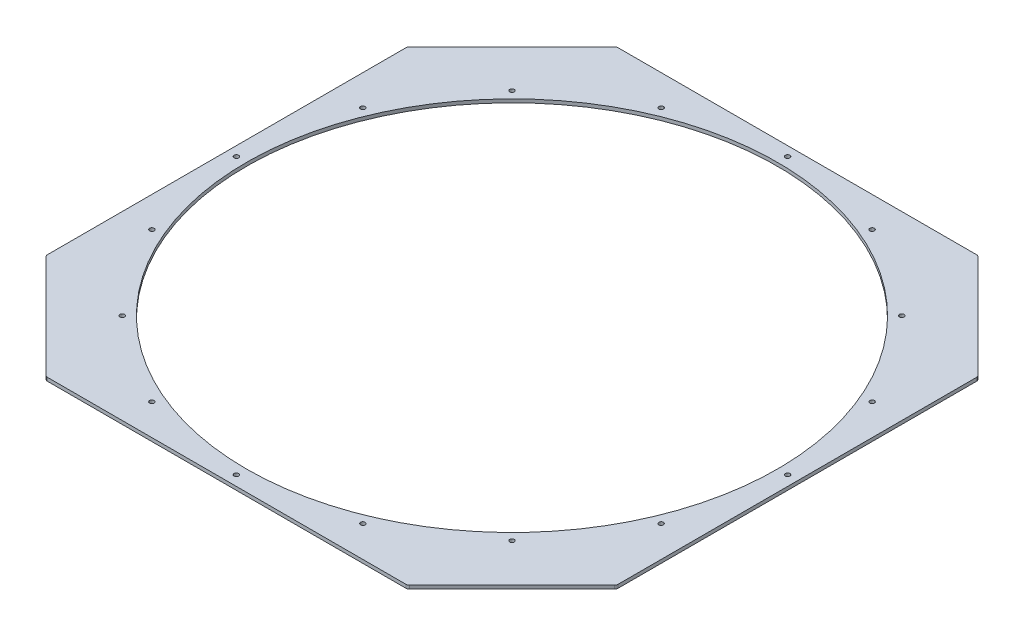
SolidWorks part; units mm, degrees
material "ASTM A36 Steel"
ref_plane "Front Plane" through (0, 0, 0) normal (0, 0, 1) x (1, 0, 0)
ref_plane "Top Plane" through (0, 0, 0) normal (0, 1, 0) x (1, 0, 0)
ref_plane "Right Plane" through (0, 0, 0) normal (1, 0, 0) x (0, 0, -1)
sketch "Sketch1" plane through (0, 0, 0) normal (0, 1, 0) x (1, 0, 0)
  line L11 (315.0665, 496.5) -> (497.5, 314.0665)
  line L13 (497.5, -315.0665) -> (315.0665, -497.5)
  line L15 (-314.0665, -497.5) -> (-496.5, -315.0665)
  line L17 (-496.5, 314.0665) -> (-314.0665, 496.5)
  line L19 (-314.0665, -497.5) -> (315.0665, -497.5)
  line L20 (-496.5, -315.0665) -> (-496.5, 314.0665)
  line L21 (-314.0665, 496.5) -> (315.0665, 496.5)
  line L22 (497.5, -315.0665) -> (497.5, 314.0665)
  line L23 (-405.7832, -405.7832) -> (405.7832, 405.7832) construction
  line L24 (-405.2832, 405.2832) -> (406.2832, -406.2832) construction
  point P6 (0, 0)
  dimension "D2" = 994
  dimension "D3" = 258
  dimension "D4" = 45
  dimension "D5" = 258
  dimension "D6" = 45
  dimension "260" = 258
  dimension "D8" = 45
  dimension "D9" = 258
  dimension "D10" = 135
  dimension "D11" = 994
  dimension "D12" = 497.5
  dimension "D13" = 497.5
extrude "Boss-Extrude1" add sketch "Sketch1" along normal blind 6
sketch "Sketch2" plane through (0, 6, 0) normal (0, 1, 0) x (1, 0, 0)
  circle A0 centre (0, 0) radius 462.5
  dimension "D1" = 925
extrude "Cut-Extrude1" cut sketch "Sketch2" against normal blind 10
sketch "Sketch3" plane through (0, 6, 0) normal (0, 1, 0) x (1, 0, 0)
  circle A0 centre (0, 0) radius 480 construction
  circle A1 centre (0, 480) radius 4
  dimension "D1" = 960
  dimension "D2" = 8
extrude "Cut-Extrude2" cut sketch "Sketch3" against normal blind 10
pattern_circular "CirPattern1" count 16 every 22.5 about axis through (0, 0, 0) along (0, 1, 0) of "Cut-Extrude2"
fillet "Fillet1" radius 6 8 edges at (-314.0665, 3, 497.5) (-496.5, 3, 315.0665) (-496.5, 3, -314.0665) (-314.0665, 3, -496.5) (315.0665, 3, -496.5) (497.5, 3, -314.0665) (497.5, 3, 315.0665) (315.0665, 3, 497.5)
